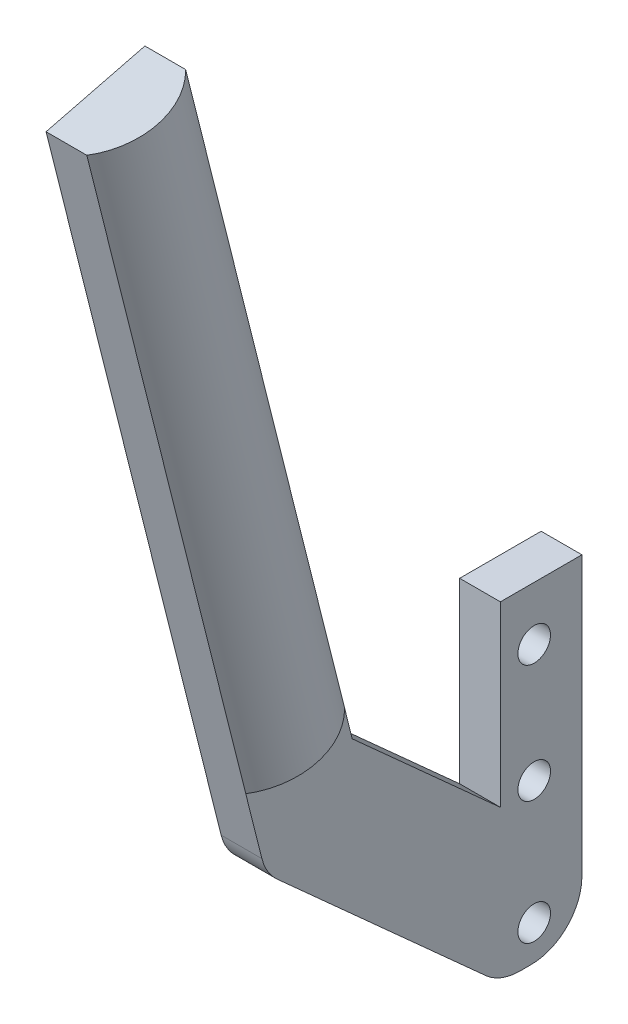
SolidWorks part; units mm, degrees
ref_plane "Ön Düzlem" through (0, 0, 0) normal (0, 0, 1) x (1, 0, 0)
ref_plane "Üst Düzlem" through (0, 0, 0) normal (0, 1, 0) x (1, 0, 0)
ref_plane "Sağ Düzlem" through (0, 0, 0) normal (1, 0, 0) x (0, 0, -1)
sketch "Çizim1" plane through (0, 0, 0) normal (0, 0, 1) x (1, 0, 0)
  line L1 (-11.5, 17.5) -> (11.5, 17.5)
  line L2 (-13.5, 15.5) -> (-13.5, -15.5)
  line L3 (-11.5, -17.5) -> (11.5, -17.5)
  line L4 (13.5, 15.5) -> (13.5, -15.5)
  circle A0 centre (-10, 14) radius 2.5
  circle A1 centre (-10, -14) radius 2.5
  circle A2 centre (10, 14) radius 2.5
  circle A3 centre (10, -14) radius 2.5
  arc A4 (11.5, -17.5) -> (13.5, -15.5) centre (11.5, -15.5) ccw
  arc A5 (-13.5, -15.5) -> (-11.5, -17.5) centre (-11.5, -15.5) ccw
  arc A6 (-11.5, 17.5) -> (-13.5, 15.5) centre (-11.5, 15.5) ccw
  arc A7 (11.5, 17.5) -> (13.5, 15.5) centre (11.5, 15.5) cw
  point P0 (0, 0)
  point P16 (13.5, -17.5)
  point P21 (-13.5, 17.5)
  point P24 (13.5, 17.5)
  dimension "D3" = 5
  dimension "D4" = 5
  dimension "D5" = 5
  dimension "D6" = 5
  dimension "D7" = 3.5
  dimension "D8" = 3.5
  dimension "D9" = 3.5
  dimension "D10" = 3.5
  dimension "D11" = 3.5
  dimension "D12" = 3.5
  dimension "D13" = 3.5
  dimension "D14" = 3.5
  dimension "D15" = 2
  dimension "D1" = 27
  dimension "D2" = 35
extrude "Yükseklik-Ekstrüzyon1" add sketch "Çizim1" along normal blind 2
sketch "Çizim2" plane through (0, 0, 0) normal (0, 0, -1) x (-1, 0, 0)
  line L0 (13.5, 15.5) -> (38.5, 15.5)
  line L1 (38.5, 15.5) -> (38.5, -15.5)
  line L2 (38.5, -15.5) -> (13.5, -15.5)
  line L3 (13.5, -15.5) -> (13.5, 15.5)
  dimension "D1" = 25
extrude "Yükseklik-Ekstrüzyon2" add sketch "Çizim2" against normal blind 2
sketch "Çizim3" plane through (0, 0, 0) normal (0, 0, -1) x (-1, 0, 0)
  line L0 (26, 15.5) -> (26, 12.3298)
  line L1 (38.5, 15.5) -> (13.5, 15.5) construction
  line L2 (26, 12.3298) -> (26.8882, 12.3298)
  line L3 (26.8882, 12.3298) -> (26.8882, 15.5)
  line L4 (26.8882, 15.5) -> (26, 15.5)
extrude "Kes-Ekstrüzyon1" cut sketch "Çizim3" against normal blind 2
mirror "Aynalama4" about plane through (-26, 15.5, 2) normal (1, 0, 0) of "Yükseklik-Ekstrüzyon1"
sketch "Çizim6" plane through (0, 0, 0) normal (0, 0, -1) x (-1, 0, 0)
  line L0 (-13.5, -15.5) -> (-13.5, 15.5) construction
  line L1 (-13.5, 15.5) -> (-16.5, 15.5)
  line L2 (-13.5, 15.5) -> (-13.5, -15.5)
  line L3 (-13.5, -15.5) -> (-16.5, -15.5)
  line L4 (-16.5, 15.5) -> (-16.5, -15.5)
  line L6 (65.5, 15.5) -> (68.5, 15.5)
  line L7 (65.5, 15.5) -> (65.5, -15.5)
  line L8 (65.5, -15.5) -> (68.5, -15.5)
  line L9 (68.5, 15.5) -> (68.5, -15.5)
  arc A0 (-11.5, 17.5) -> (-13.5, 15.5) centre (-11.5, 15.5) ccw construction
  dimension "D1" = 3
  dimension "D2" = 3
extrude "Yükseklik-Ekstrüzyon3" add sketch "Çizim6" against normal blind 10
sketch "Çizim7" plane through (16.5, 0, 0) normal (1, 0, 0) x (0, 0, -1)
  circle A0 centre (-6.6819, 11.5752) radius 1.6
  circle A1 centre (-6.6819, 0) radius 1.6
  circle A2 centre (-6.6819, -12.0698) radius 1.6
  dimension "D1" = 3.2
  dimension "D2" = 3.2
  dimension "D3" = 3.2
extrude "Kes-Ekstrüzyon2" cut sketch "Çizim7" against normal blind 141
sketch "Çizim8" plane through (0, 0, 0) normal (0, 0, -1) x (-1, 0, 0)
  line L0 (26, 15.5) -> (13.5, 15.5) construction
  line L1 (24.5276, 15.5) -> (29.0801, 15.5)
  line L2 (24.5276, 15.5) -> (24.5276, 9.757)
  line L3 (24.5276, 9.757) -> (29.0801, 9.757)
  line L4 (29.0801, 15.5) -> (29.0801, 9.757)
extrude "Yükseklik-Ekstrüzyon4" add sketch "Çizim8" against normal blind 2
sketch "Çizim9" plane through (0, -15.5, 0) normal (0, -1, 0) x (1, 0, 0)
  line L0 (-13.5, 2) -> (-38.5, 2) construction
  line L1 (-68.5, 10) -> (-65.5, 10)
  line L2 (13.5, 10) -> (16.5, 10)
  arc A0 (-65.5, 10) -> (13.5, 10) centre (-26, 1.6211) cw
  arc A1 (-68.5, 10) -> (16.5, 10) centre (-26, 0.4375) cw
  point P7 (-26, 42)
  point P11 (-26, 44)
  dimension "D1" = 40
  dimension "D2" = 42
extrude "Yükseklik-Ekstrüzyon5" add sketch "Çizim9" against normal up to surface (31 mm away) up to face at (14.7, 15.5, 4.4)
sketch "Çizim10" plane through (0, 0, 0) normal (0, 0, -1) x (-1, 0, 0)
  line L0 (-16.5, 15.5) -> (-16.5, 19.8453)
  line L1 (-16.5, 19.8453) -> (68.5, 19.8453)
  line L2 (68.5, 19.8453) -> (68.5, 15.5)
  line L12 (38.5, 15.5) -> (13.5, 15.5)
  line L13 (11.5, 17.5) -> (-11.5, 17.5)
  line L14 (-13.5, 15.5) -> (-16.5, 15.5)
  line L15 (-16.5, 15.5) -> (-16.5, -15.5)
  line L16 (-16.5, -15.5) -> (-13.5, -15.5)
  line L17 (-11.5, -17.5) -> (11.5, -17.5)
  line L18 (13.5, -15.5) -> (38.5, -15.5)
  line L19 (40.5, -17.5) -> (63.5, -17.5)
  line L20 (65.5, -15.5) -> (68.5, -15.5)
  line L21 (68.5, -15.5) -> (68.5, 15.5)
  line L22 (68.5, 15.5) -> (65.5, 15.5)
  line L23 (63.5, 17.5) -> (40.5, 17.5)
  line L24 (38.5, 15.5) -> (13.5, 15.5)
  line L25 (11.5, 17.5) -> (-11.5, 17.5)
  line L26 (-13.5, 15.5) -> (-16.5, 15.5)
  line L27 (-16.5, 15.5) -> (-16.5, -15.5)
  line L28 (-16.5, -15.5) -> (-13.5, -15.5)
  line L29 (-11.5, -17.5) -> (11.5, -17.5)
  line L30 (13.5, -15.5) -> (38.5, -15.5)
  line L31 (40.5, -17.5) -> (63.5, -17.5)
  line L32 (65.5, -15.5) -> (68.5, -15.5)
  line L33 (68.5, -15.5) -> (68.5, 15.5)
  line L34 (68.5, 15.5) -> (65.5, 15.5)
  line L35 (63.5, 17.5) -> (40.5, 17.5)
  arc A8 (13.5, 15.5) -> (11.5, 17.5) centre (11.5, 15.5) ccw
  arc A9 (-11.5, 17.5) -> (-13.5, 15.5) centre (-11.5, 15.5) ccw
  arc A10 (-13.5, -15.5) -> (-11.5, -17.5) centre (-11.5, -15.5) ccw
  arc A11 (11.5, -17.5) -> (13.5, -15.5) centre (11.5, -15.5) ccw
  arc A12 (38.5, -15.5) -> (40.5, -17.5) centre (40.5, -15.5) ccw
  arc A13 (63.5, -17.5) -> (65.5, -15.5) centre (63.5, -15.5) ccw
  arc A14 (65.5, 15.5) -> (63.5, 17.5) centre (63.5, 15.5) ccw
  arc A15 (40.5, 17.5) -> (38.5, 15.5) centre (40.5, 15.5) ccw
  arc A16 (13.5, 15.5) -> (11.5, 17.5) centre (11.5, 15.5) ccw
  arc A17 (-11.5, 17.5) -> (-13.5, 15.5) centre (-11.5, 15.5) ccw
  arc A18 (-13.5, -15.5) -> (-11.5, -17.5) centre (-11.5, -15.5) ccw
  arc A19 (11.5, -17.5) -> (13.5, -15.5) centre (11.5, -15.5) ccw
  arc A20 (38.5, -15.5) -> (40.5, -17.5) centre (40.5, -15.5) ccw
  arc A21 (63.5, -17.5) -> (65.5, -15.5) centre (63.5, -15.5) ccw
  arc A22 (65.5, 15.5) -> (63.5, 17.5) centre (63.5, 15.5) ccw
  arc A23 (40.5, 17.5) -> (38.5, 15.5) centre (40.5, 15.5) ccw
  line M21 (38.5, 15.5) -> (13.5, 15.5)
  arc M22 (13.5, 15.5) -> (11.5, 17.5) centre (11.5, 15.5) ccw
  line M23 (11.5, 17.5) -> (-11.5, 17.5)
  arc M24 (-11.5, 17.5) -> (-13.5, 15.5) centre (-11.5, 15.5) ccw
  line M25 (-13.5, 15.5) -> (-16.5, 15.5)
  line M37 (68.5, 15.5) -> (65.5, 15.5)
  arc M38 (65.5, 15.5) -> (63.5, 17.5) centre (63.5, 15.5) ccw
  line M39 (63.5, 17.5) -> (40.5, 17.5)
  arc M40 (40.5, 17.5) -> (38.5, 15.5) centre (40.5, 15.5) ccw
  dimension "D1" = 0
extrude "Yükseklik-Ekstrüzyon6" add sketch "Çizim10" against normal up to surface (10 mm away) contours L2 L1 L0 M25 M24 M23 M22 M21 M40 M39 M38 M37
fillet "Radyus1" radius 3 3 edges at (16.5, 19.8453, 5) (-68.5, 19.8453, 5) (-26, 19.8453, 44)
fillet "Radyus2" radius 2 5 edges at (16.5, 0.6726, 0) (15.6213, 18.9666, 0) (-68.5, 0.6726, 0) (-67.6213, 18.9666, 0) (-26, 19.8453, 0)
sketch "Çizim11" plane through (0, 0, 0) normal (0, 0, -1) x (-1, 0, 0)
  line L0 (66.5, -15.5) -> (66.5, 16.8453) construction
  line L1 (39, 11) -> (64, 11)
  line L2 (39, 11) -> (39, -9)
  line L3 (39, -9) -> (64, -9)
  line L4 (64, 11) -> (64, -9)
  line L5 (-12, 11) -> (13, 11)
  line L6 (-12, 11) -> (-12, -9)
  line L7 (-12, -9) -> (13, -9)
  line L8 (13, 11) -> (13, -9)
  line L9 (-14.5, 16.8453) -> (-14.5, -15.5) construction
  circle A0 centre (62, -14) radius 2.5 construction
  circle A1 centre (10, -14) radius 2.5 construction
  dimension "D1" = 25
  dimension "D2" = 20
  dimension "D3" = 5
  dimension "D4" = 5
  dimension "D5" = 25
  dimension "D6" = 2.5
  dimension "D7" = 2.5
  dimension "D8" = 20
extrude "Kes-Ekstrüzyon3" cut sketch "Çizim11" against normal blind 10
sketch "Çizim12" plane through (0, 0, 0) normal (0, 0, -1) x (-1, 0, 0)
  line L0 (11.5, -17.5) -> (40.5, -17.5)
  line L9 (-14.5, 16.8453) -> (-14.5, -15.5)
  line L10 (-14.5, -15.5) -> (-13.5, -15.5)
  line L11 (-11.5, -17.5) -> (11.5, -17.5)
  line L12 (13.5, -15.5) -> (38.5, -15.5)
  line L13 (40.5, -17.5) -> (63.5, -17.5)
  line L14 (65.5, -15.5) -> (66.5, -15.5)
  line L15 (66.5, -15.5) -> (66.5, 16.8453)
  line L16 (65.5, 17.8453) -> (-13.5, 17.8453)
  line L17 (-14.5, 16.8453) -> (-14.5, -15.5)
  line L18 (-14.5, -15.5) -> (-13.5, -15.5)
  line L19 (-11.5, -17.5) -> (11.5, -17.5)
  line L20 (13.5, -15.5) -> (38.5, -15.5)
  line L21 (40.5, -17.5) -> (63.5, -17.5)
  line L22 (65.5, -15.5) -> (66.5, -15.5)
  line L23 (66.5, -15.5) -> (66.5, 16.8453)
  line L24 (65.5, 17.8453) -> (-13.5, 17.8453)
  arc A6 (-13.5, 17.8453) -> (-14.5, 16.8453) centre (-13.5, 16.8453) ccw
  arc A7 (-13.5, -15.5) -> (-11.5, -17.5) centre (-11.5, -15.5) ccw
  arc A8 (11.5, -17.5) -> (13.5, -15.5) centre (11.5, -15.5) ccw
  arc A9 (38.5, -15.5) -> (40.5, -17.5) centre (40.5, -15.5) ccw
  arc A10 (63.5, -17.5) -> (65.5, -15.5) centre (63.5, -15.5) ccw
  arc A11 (66.5, 16.8453) -> (65.5, 17.8453) centre (65.5, 16.8453) ccw
  arc A12 (-13.5, 17.8453) -> (-14.5, 16.8453) centre (-13.5, 16.8453) ccw
  arc A13 (-13.5, -15.5) -> (-11.5, -17.5) centre (-11.5, -15.5) ccw
  arc A14 (11.5, -17.5) -> (13.5, -15.5) centre (11.5, -15.5) ccw
  arc A15 (38.5, -15.5) -> (40.5, -17.5) centre (40.5, -15.5) ccw
  arc A16 (63.5, -17.5) -> (65.5, -15.5) centre (63.5, -15.5) ccw
  arc A17 (66.5, 16.8453) -> (65.5, 17.8453) centre (65.5, 16.8453) ccw
  arc M28 (11.5, -17.5) -> (13.5, -15.5) centre (11.5, -15.5) ccw
  line M29 (13.5, -15.5) -> (38.5, -15.5)
  arc M30 (38.5, -15.5) -> (40.5, -17.5) centre (40.5, -15.5) ccw
  dimension "D1" = 0
extrude "Yükseklik-Ekstrüzyon7" add sketch "Çizim12" against normal up to surface (2 mm away) contours L0 M28 M30 M29
sketch "Çizim13" plane through (16.5, 0, 0) normal (1, 0, 0) x (0, 0, -1)
  line L0 (-10, -15.5) -> (-33.0348, 5.2381)
  line L1 (-33.0348, 5.2381) -> (-50.5893, 75.0972)
  line L2 (-50.5893, 75.0972) -> (-40.8908, 77.5343)
  line L3 (-40.8908, 77.5343) -> (-24.5417, 12.472)
  line L4 (-10, -15.5) -> (-2, -15.5)
  line L5 (-2, -15.5) -> (-2, 16.8453)
  line L6 (-2, 16.8453) -> (-10, 16.8453)
  line L7 (-10, 16.8453) -> (-10, -15.5)
  line L8 (-10, -15.5) -> (-2, -15.5)
  line L9 (-2, -15.5) -> (-2, 16.8453)
  line L10 (-2, 16.8453) -> (-10, 16.8453)
  line L11 (-10, 16.8453) -> (-10, -15.5)
  line L12 (-24.5417, 12.472) -> (-10, -0.6198)
  circle A0 centre (-6.6819, -12.0698) radius 1.6 construction
  circle A1 centre (-6.6819, 0) radius 1.6 construction
  circle A2 centre (-6.6819, 11.5752) radius 1.6 construction
  circle A3 centre (-6.6819, -12.0698) radius 1.6
  circle A4 centre (-6.6819, 0) radius 1.6
  circle A5 centre (-6.6819, 11.5752) radius 1.6
  point P17 (-50.5893, 75.0972)
  circle M5 centre (-6.6819, 0) radius 1.6
  circle M6 centre (-6.6819, -12.0698) radius 1.6
  circle M7 centre (-6.6819, 11.5752) radius 1.6
  line M8 (-10, -15.5) -> (-2, -15.5)
  line M9 (-2, -15.5) -> (-2, 16.8453)
  line M10 (-2, 16.8453) -> (-10, 16.8453)
  line M11 (-10, 16.8453) -> (-10, -15.5)
  dimension "D2" = 10
  dimension "D1" = 0
extrude "Yükseklik-Ekstrüzyon8" add sketch "Çizim13" along normal blind 4 contours L11 M11 M8 M9 M10 M6 M7 M5 | L12 L3 L2 L1 L0 L11
sketch "Çizim14" plane through (16.5, 0, 0) normal (-1, 0, 0) x (0, 0, 1)
  line L1 (-42.7195, 57.5579) -> (84.0616, 57.5579)
  line L2 (-42.7195, 57.5579) -> (-42.7195, -25.2653)
  line L3 (-42.7195, -25.2653) -> (84.0616, -25.2653)
  line L4 (84.0616, 57.5579) -> (84.0616, -25.2653)
extrude "Kes-Ekstrüzyon4" cut sketch "Çizim14" along normal blind 164
sketch "Çizim15" plane through (0, 82.5942, 20.7546) normal (0, 0.9698, 0.2437) x (1, 0, 0)
  line L0 (20.5, -20.7622) -> (20.5, -30.7622)
  arc A0 (20.5, -20.7622) -> (20.5, -30.7622) centre (15.5, -25.7622) cw
extrude "Yükseklik-Ekstrüzyon9" add sketch "Çizim15" against normal blind 64
fillet "Radyus3" radius 5 3 edges at (18.5, -15.5, 2) (18.5, 5.2381, 33.0348) (18.5, -15.5, 10)
